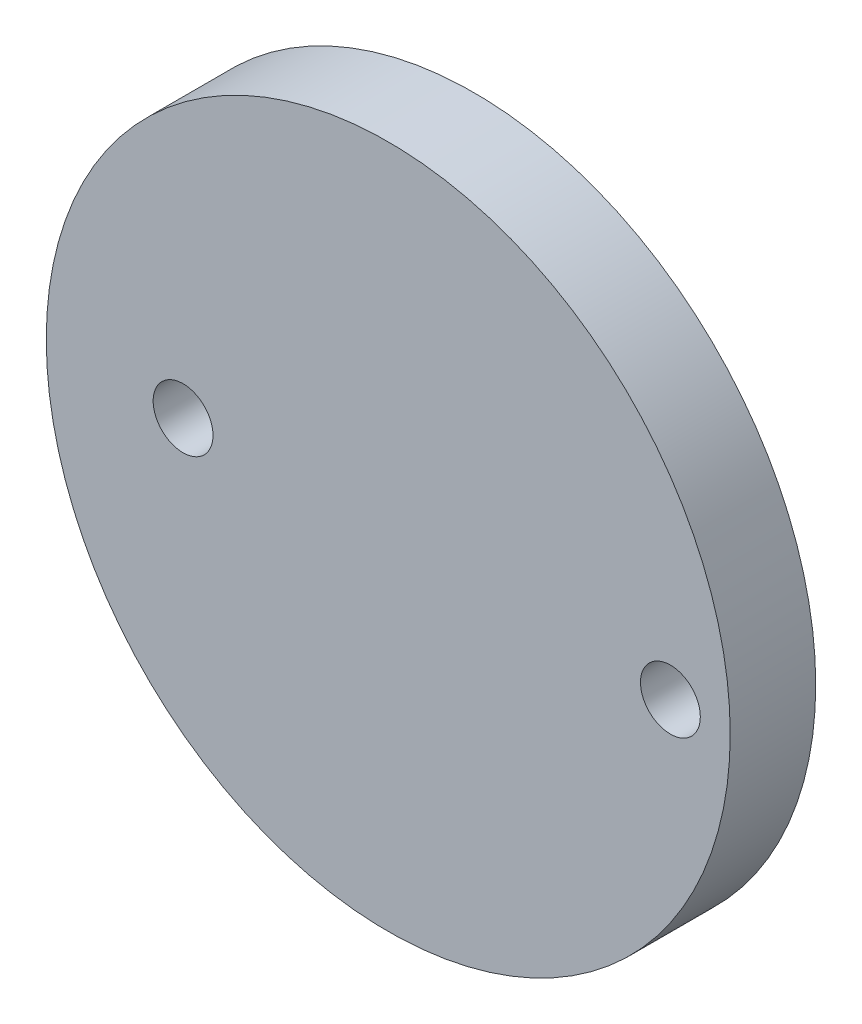
SolidWorks part; units mm, degrees
ref_plane "Front Plane" through (0, 0, 0) normal (0, 0, 1) x (1, 0, 0)
ref_plane "Top Plane" through (0, 0, 0) normal (0, 1, 0) x (1, 0, 0)
ref_plane "Right Plane" through (0, 0, 0) normal (1, 0, 0) x (0, 0, -1)
sketch "Sketch1" plane through (0, 0, 0) normal (0, 0, 1) x (1, 0, 0)
  circle A0 centre (0, 0) radius 20
  dimension "D1" = 40
extrude "Boss-Extrude1" add sketch "Sketch1" along normal blind 5
sketch "Sketch2" plane through (0, 0, 5) normal (0, 0, 1) x (1, 0, 0)
  line L0 (0, 0) -> (20, 0) construction
  line L1 (-12, 0) -> (0, 0) construction
  circle A0 centre (0, 0) radius 20 construction
  circle A1 centre (16.5, 0) radius 1.75
  circle A2 centre (-12, 0) radius 1.75
  dimension "D1" = 3.5
  dimension "D4" = 3.5
  dimension "D2" = 16.5
  dimension "D3" = 12
extrude "Cut-Extrude1" cut sketch "Sketch2" against normal through all
